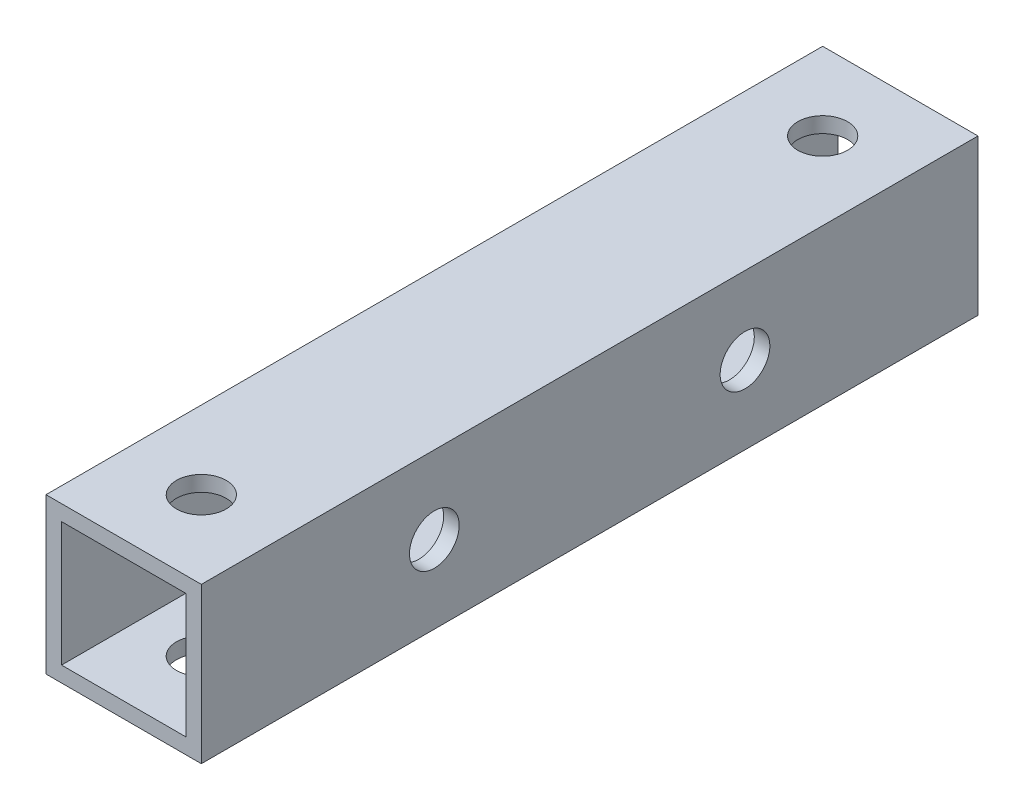
SolidWorks part; units mm, degrees
ref_plane "正面" through (0, 0, 0) normal (0, 0, 1) x (1, 0, 0)
ref_plane "平面" through (0, 0, 0) normal (0, 1, 0) x (1, 0, 0)
ref_plane "右側面" through (0, 0, 0) normal (1, 0, 0) x (0, 0, -1)
sketch "ｽｹｯﾁ1" plane through (0, 0, 0) normal (0, 0, 1) x (1, 0, 0)
  line L0 (-4, 4) -> (-4, -4)
  line L1 (-5, 5) -> (5, 5)
  line L2 (-5, 5) -> (-5, -5)
  line L3 (-5, -5) -> (5, -5)
  line L4 (5, 5) -> (5, -5)
  line L5 (-5, 5) -> (5, -5) construction
  line L6 (-5, -5) -> (5, 5) construction
  line L7 (-4, -4) -> (4, -4)
  line L8 (4, 4) -> (4, -4)
  line L9 (-4, 4) -> (4, 4)
  point P0 (0, 0)
  dimension "D1" = 10
  dimension "D2" = 10
  dimension "D3" = 1
extrude "ﾎﾞｽ - 押し出し1" add sketch "ｽｹｯﾁ1" along normal blind 50
sketch "ｽｹｯﾁ2" plane through (0, 5, 0) normal (0, 1, 0) x (1, 0, 0)
  line L0 (0, -5.5) -> (0, 5.5) construction
  line L1 (5, -50) -> (-5, -50) construction
  line L2 (-5.5, 0) -> (5.5, 0) construction
  circle A0 centre (0, -45) radius 1.6
  circle A1 centre (0, -5) radius 1.6
  dimension "D1" = 3.2
  dimension "D2" = 3.2
  dimension "D3" = 5
  dimension "D4" = 5
extrude "ｶｯﾄ - 押し出し1" cut sketch "ｽｹｯﾁ2" against normal through all
sketch "ｽｹｯﾁ3" plane through (-5, 0, 0) normal (-1, 0, 0) x (0, 0, 1)
  line L0 (5.5, 0) -> (-5.5, 0) construction
  line L1 (0, -5.5) -> (0, 5.5) construction
  line L2 (50, 5) -> (50, -5) construction
  circle A0 centre (15, 0) radius 1.6
  circle A1 centre (35, 0) radius 1.6
  dimension "D1" = 3.2
  dimension "D2" = 15
  dimension "D3" = 3.2
  dimension "D4" = 15
extrude "ｶｯﾄ - 押し出し2" cut sketch "ｽｹｯﾁ3" against normal through all
